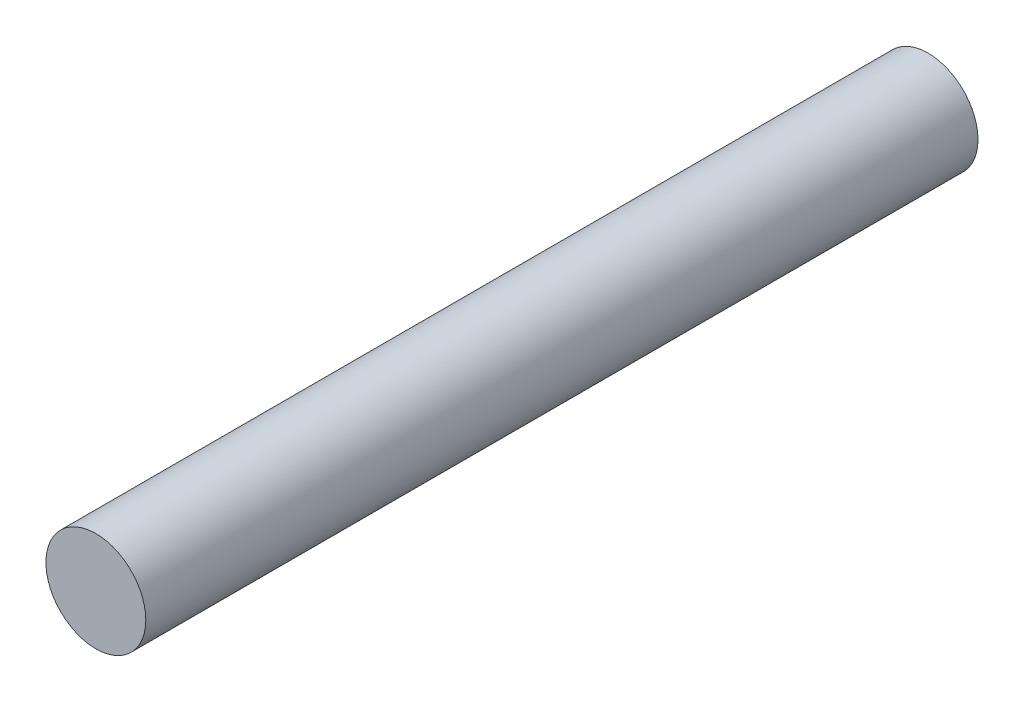
SolidWorks part; units mm, degrees
ref_plane "Ön Düzlem" through (0, 0, 0) normal (0, 0, 1) x (1, 0, 0)
ref_plane "Üst Düzlem" through (0, 0, 0) normal (0, 1, 0) x (1, 0, 0)
ref_plane "Sağ Düzlem" through (0, 0, 0) normal (1, 0, 0) x (0, 0, -1)
sketch "Sketch1" plane through (0, 0, 0) normal (0, 0, 1) x (1, 0, 0)
  circle A0 centre (0, 0) radius 1.5
  dimension "D1" = 3
extrude "Boss-Extrude1" add sketch "Sketch1" along normal blind 25
